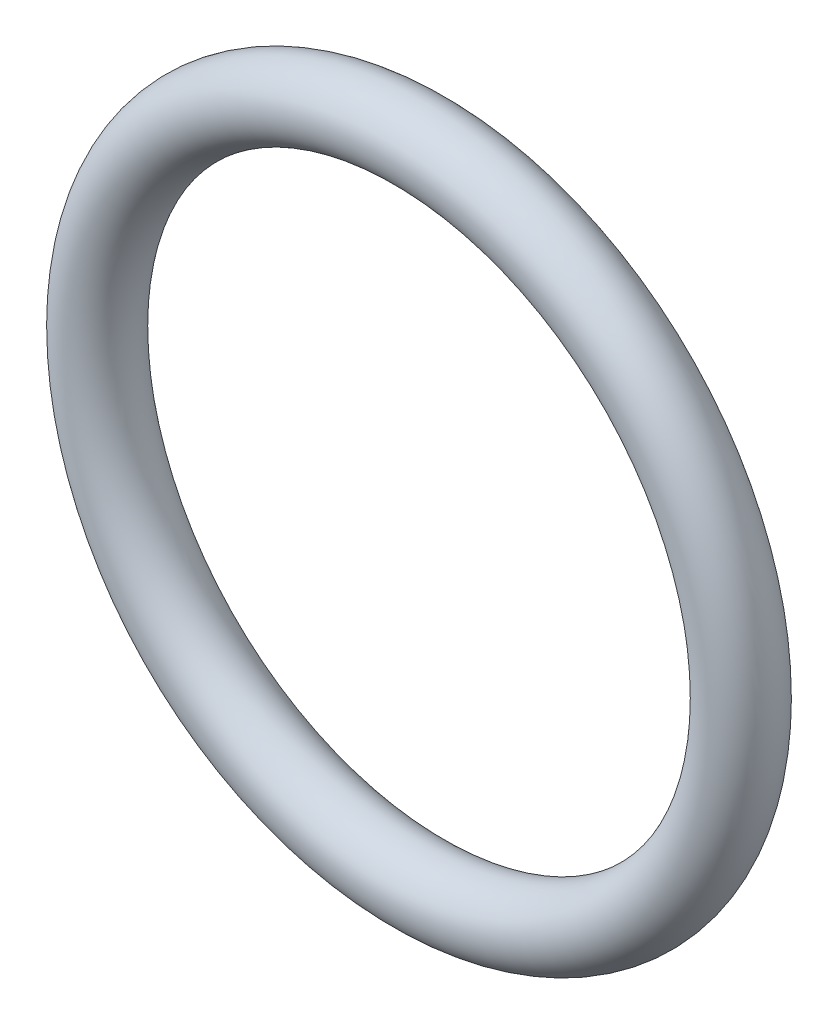
SolidWorks part; units mm, degrees
ref_plane "Front" through (0, 0, 0) normal (0, 0, 1) x (1, 0, 0)
ref_plane "Top" through (0, 0, 0) normal (0, 1, 0) x (1, 0, 0)
ref_plane "Right" through (0, 0, 0) normal (1, 0, 0) x (0, 0, -1)
sketch "Sketch1" plane through (0, 0, 0) normal (1, 0, 0) x (0, -1, 0)
  line L0 (0, -1.5) -> (0, 1.5) construction
  line L2 (-16.5, 0) -> (16.5, 0) construction
  line L3 (-12, 0) -> (12, 0) construction
  circle A0 centre (13.5, 0) radius 1.5
  point P9 (12, 0)
  point P10 (15, 0)
  point P13 (13.5, 1.5)
  point P14 (13.5, -1.5)
  dimension "Width" = 3
  dimension "ID" = 24
revolve "Revolve1" add sketch "Sketch1" angle 360 about L0
